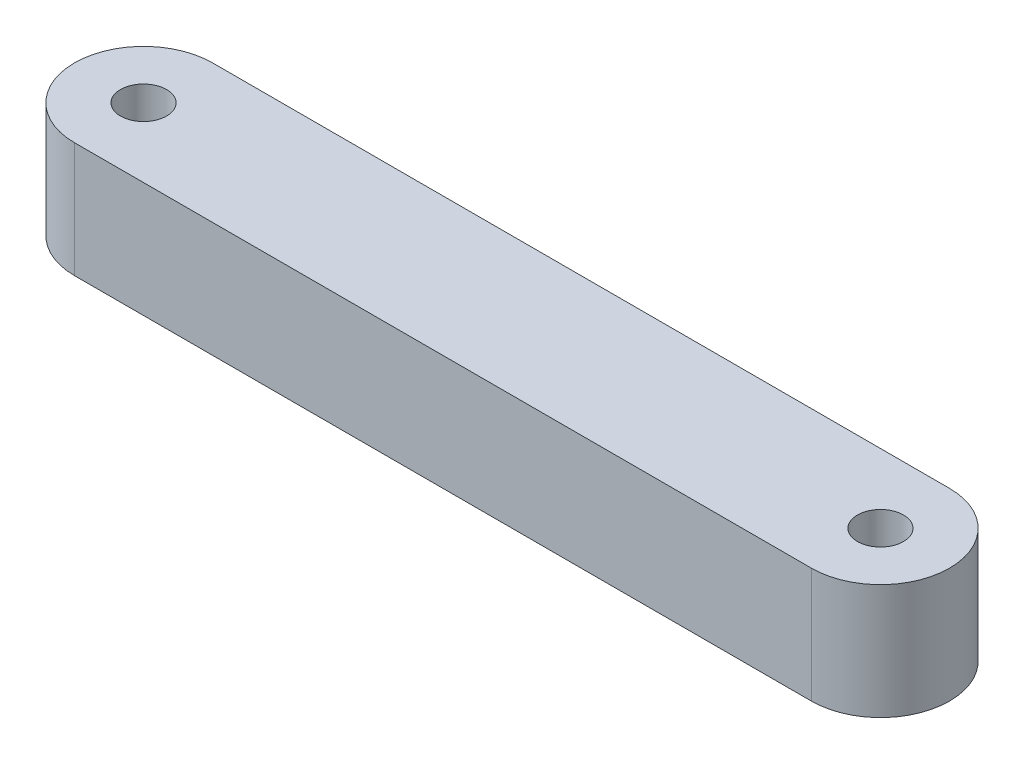
SolidWorks part; units mm, degrees
ref_plane "Front Plane" through (0, 0, 0) normal (0, 0, 1) x (1, 0, 0)
ref_plane "Top Plane" through (0, 0, 0) normal (0, 1, 0) x (1, 0, 0)
ref_plane "Right Plane" through (0, 0, 0) normal (1, 0, 0) x (0, 0, -1)
sketch "Sketch3" plane through (0, 0, 0) normal (0, 1, 0) x (1, 0, 0)
  line L0 (-50.8, 0) -> (30.48, 0) construction
  line L1 (-6.985, 0) -> (6.985, 0) construction
  line L2 (-50.8, 7.62) -> (30.48, 7.62)
  line L3 (-50.8, -7.62) -> (30.48, -7.62)
  arc A0 (-50.8, 7.62) -> (-50.8, -7.62) centre (-50.8, 0) ccw
  arc A1 (30.48, -7.62) -> (30.48, 7.62) centre (30.48, 0) ccw
  point P5 (-10.16, 0)
  point P10 (0, 0)
  dimension "D2" = 7.62
  dimension "D1" = 81.28
  dimension "D3" = 50.8
extrude "Boss-Extrude1" add sketch "Sketch3" along normal blind 12.7
sketch "Sketch4" plane through (0, 12.7, 0) normal (0, 1, 0) x (1, 0, 0)
  circle A0 centre (-50.8, 0) radius 2.54
  circle A1 centre (30.48, 0) radius 2.54
  point P3 (0, 0)
  dimension "D1" = 5.08
extrude "Cut-Extrude3" cut sketch "Sketch4" against normal through all
equation "\"TibiaLength\"= 4in"
equation "\"TibiaRadius\"= 0.3in"
equation "\"TibiaDistFromCentre\"= \"TibiaLength\" / 2"
equation "\"TibiaThickness\"= 0.5in"
equation "\"HoleRadius\"= 0.2in"
equation "\"D1@Sketch3\"= \"TibiaLength\" * 0.8"
equation "\"D2@Sketch3\"= \"TibiaRadius\""
equation "\"D3@Sketch3\"= \"TibiaDistFromCentre\""
equation "\"D1@Boss-Extrude1\"= \"TibiaThickness\""
equation "\"D1@Sketch4\"= \"HoleRadius\""
